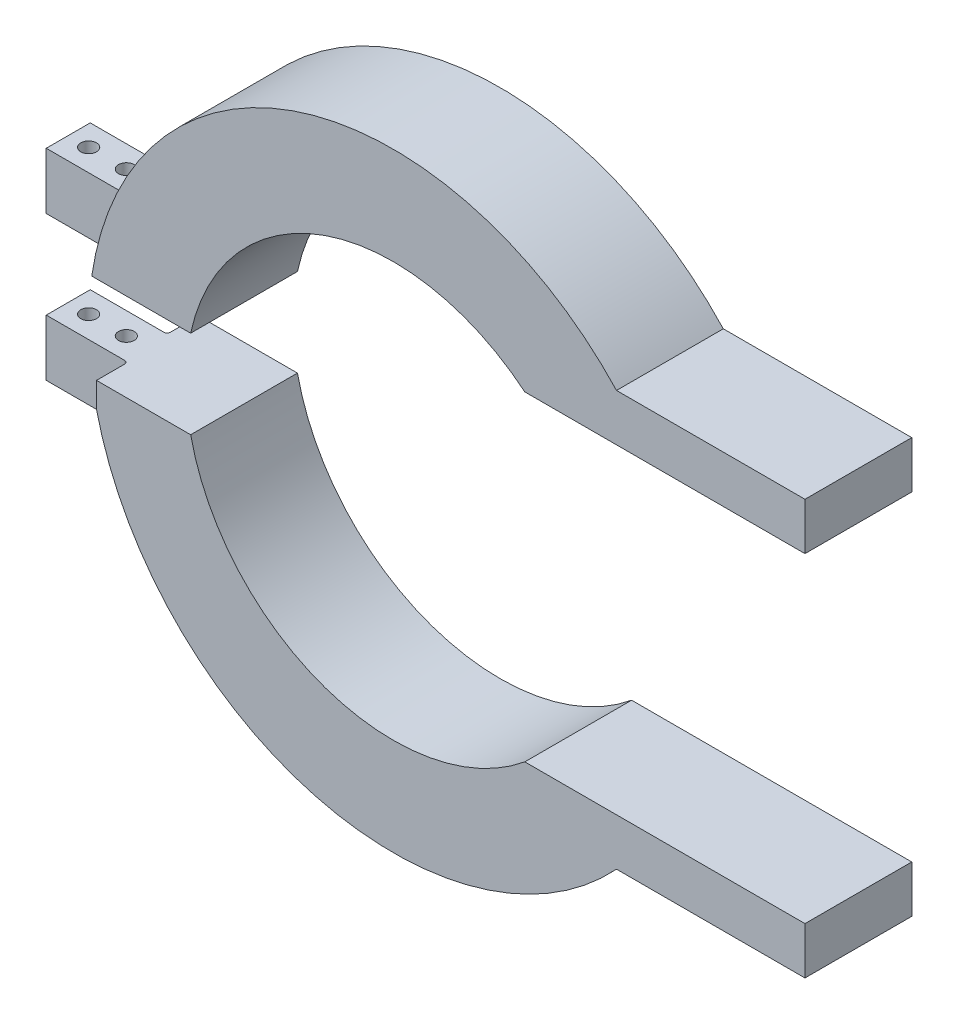
SolidWorks part; units mm, degrees
ref_plane "Front Plane" through (0, 0, 0) normal (0, 0, 1) x (1, 0, 0)
ref_plane "Top Plane" through (0, 0, 0) normal (0, 1, 0) x (1, 0, 0)
ref_plane "Right Plane" through (0, 0, 0) normal (1, 0, 0) x (0, 0, -1)
sketch "Sketch1" plane through (0, 0, 0) normal (0, 0, 1) x (1, 0, 0)
  line L0 (0, 0) -> (-48.5, 0) construction
  line L4 (35.5422, -33) -> (65.5422, -33)
  line L14 (-60.2361, -11) -> (-60.2361, -7)
  line L15 (20.9464, 25.5) -> (65.5422, 25.5)
  line L16 (20.9464, -25.5) -> (65.5422, -25.5)
  line L17 (65.5422, -33) -> (65.5422, -25.5)
  line L18 (-60.2361, 7) -> (-60.2361, 11)
  line L19 (0, 0) -> (88.5794, 0)
  line L21 (-47.2361, -11) -> (-60.2361, -11)
  line L22 (35.5422, 33) -> (65.5422, 33)
  line L23 (65.5422, 33) -> (65.5422, 25.5)
  line L25 (-60.2361, -7) -> (-32.249, -7)
  line L26 (-60.2361, 7) -> (-32.2494, 6.9983)
  line L27 (-47.2361, 11) -> (-60.2361, 11)
  arc A3 (35.5422, 33) -> (-47.2361, 11) centre (0, 0) ccw
  arc A5 (-47.2361, -11) -> (35.5422, -33) centre (0, 0) ccw
  arc A7 (20.9464, 25.5) -> (-32.2494, 6.9983) centre (0, 0) ccw
  arc A8 (-32.249, -7) -> (20.9464, -25.5) centre (0, 0) ccw
  point P17 (-48.5, 0)
  dimension "D1" = 48.5
  dimension "D6" = 7.5
  dimension "D4" = 48.5
  dimension "D5" = 66
  dimension "D3" = 30
  dimension "D7" = 4
  dimension "D2" = 51
  dimension "D8" = 22
  dimension "D9" = 13
extrude "Boss-Extrude1" add sketch "Sketch1" along normal blind 7 contours A7 L15 L23 L22 A3 L27 L18 L26 | A8 L25 L14 L21 A5 L4 L17 L16
sketch "Sketch2" plane through (0, 11, 0) normal (0, 1, 0) x (1, 0, 0)
  line L0 (-47.2361, -3.5) -> (-50.9861, -3.5) construction
  line L1 (-47.2361, -7) -> (-47.2361, 0) construction
  line L2 (-47.2361, -3.5) -> (-47.2361, 0) construction
  line L3 (-50.9861, -3.5) -> (-56.9861, -3.5) construction
  circle A0 centre (-50.9861, -3.5) radius 1.25
  circle A1 centre (-56.9861, -3.5) radius 1.25
  dimension "D2" = 6
  dimension "D3" = 2.5
  dimension "D4" = 2.5
  dimension "D1" = 3.75
sketch "Sketch7" plane through (0, 0, 7) normal (0, 0, 1) x (1, 0, 0)
  line L0 (-47.2361, -11) -> (-47.2361, -7)
  line L1 (-60.2361, -7) -> (-32.249, -7) construction
  line L2 (-47.2361, -7) -> (-32.249, -7)
  line L3 (35.5422, -33) -> (65.5422, -33)
  line L4 (65.5422, -33) -> (65.5422, -25.5) construction
  line L5 (35.5422, -33) -> (65.5422, -33) construction
  line L6 (65.5422, -33) -> (65.5422, -25.5)
  line L7 (20.9464, -25.5) -> (65.5422, -25.5)
  line L8 (20.9464, 25.5) -> (65.5422, 25.5)
  line L9 (20.9464, 25.5) -> (65.5422, 25.5) construction
  line L10 (65.5422, 25.5) -> (65.5422, 33)
  line L11 (65.5422, 33) -> (35.5422, 33)
  line L12 (-32.2494, 6.9983) -> (-47.9923, 6.9993)
  line L13 (-60.2361, 7) -> (-32.2494, 6.9983) construction
  arc A0 (-32.249, -7) -> (20.9464, -25.5) centre (0, 0) ccw
  arc A1 (-47.2361, -11) -> (35.5422, -33) centre (0, 0) ccw
  arc A2 (20.9464, 25.5) -> (-32.2494, 6.9983) centre (0, 0) ccw
  arc A3 (35.5422, 33) -> (-47.9923, 6.9993) centre (0, 0) ccw
extrude "Boss-Extrude2" add sketch "Sketch7" along normal blind 5
sketch "Sketch8" plane through (0, 0, 0) normal (0, 0, -1) x (-1, 0, 0)
  line L0 (32.249, -7) -> (47.9922, -7)
  line L1 (60.2361, -7) -> (32.249, -7) construction
  line L2 (-20.9464, -25.5) -> (-65.5422, -25.5)
  line L3 (-65.5422, -25.5) -> (-65.5422, -33)
  line L4 (-65.5422, -33) -> (-35.5422, -33)
  line L5 (-35.5422, -33) -> (-65.5422, -33) construction
  line L6 (-3.3458, 0) -> (4.69, 0)
  line L7 (32.249, 7) -> (47.9922, 7)
  line L8 (-20.9464, 25.5) -> (-65.5422, 25.5)
  line L9 (-65.5422, 25.5) -> (-65.5422, 33)
  line L10 (-65.5422, 33) -> (-35.5422, 33)
  arc A0 (-20.9464, -25.5) -> (32.249, -7) centre (0, 0) ccw
  arc A3 (-35.5422, -33) -> (47.9922, -7) centre (0, 0) ccw
  arc A4 (47.9922, 7) -> (-35.5422, 33) centre (0, 0) ccw
  arc A5 (32.249, 7) -> (-20.9464, 25.5) centre (0, 0) ccw
  arc M5 (32.249, -7) -> (-20.9464, -25.5) centre (0, 0) cw
  line M6 (-20.9464, -25.5) -> (-65.5422, -25.5)
  line M7 (-65.5422, -25.5) -> (-65.5422, -33)
  line M8 (-65.5422, -33) -> (-35.5422, -33)
  arc M9 (-35.5422, -33) -> (47.2361, -11) centre (0, 0) ccw
  line M12 (60.2361, -7) -> (32.249, -7)
extrude "Boss-Extrude3" add sketch "Sketch8" along normal blind 5 contours A5 L7 A4 L10 L9 L8 | A3 M9 M12 M5 M6 M7 M8
sketch "Sketch9" plane through (0, 11, 0) normal (0, 1, 0) x (1, 0, 0)
  line L0 (-47.2361, 0) -> (-60.2361, 0)
  line L1 (-60.2361, 0) -> (-60.2361, -7)
  line L2 (-60.2361, -7) -> (-47.2361, -7)
  line L3 (-47.2361, -7) -> (-47.2361, 0)
extrude "Boss-Extrude4" add sketch "Sketch9" along normal blind 5
sketch "Sketch10" plane through (0, -11, 0) normal (0, -1, 0) x (-1, 0, 0)
  line L0 (60.2361, -7) -> (60.2361, 0)
  line L1 (60.2361, 0) -> (47.2361, 0)
  line L2 (47.2361, 0) -> (47.2361, -7)
  line L3 (47.2361, -7) -> (60.2361, -7)
extrude "Boss-Extrude5" add sketch "Sketch10" along normal blind 5
sketch "Sketch11" plane through (0, 16, 0) normal (0, 1, 0) x (1, 0, 0)
  line L0 (-50.9861, -3.5) -> (-47.2361, -3.5) construction
  line L1 (-47.2361, -3.5) -> (-47.2361, 0) construction
  line L2 (-56.9861, -3.5) -> (-50.9861, -3.5) construction
  circle A0 centre (-56.9861, -3.5) radius 1.25
  circle A1 centre (-50.9861, -3.5) radius 1.25
extrude "Cut-Extrude2" cut sketch "Sketch11" against normal up to surface (32 mm away) up to face at (-53.7361, -16, 3.5)
sketch "Sketch12" plane through (-47.2361, 0, 0) normal (1, 0, 0) x (0, 0, -1)
  line L0 (0, 11) -> (0, 16)
  line L1 (-3.5, 11) -> (0, 11) construction
  line L2 (0, 16) -> (-7, 16)
  line L3 (-7, 16) -> (-7, 11)
  line L4 (-7, 16) -> (-7, 11) construction
  line L5 (-7, 11) -> (0, 11)
  line L6 (1.5401, 0) -> (-3.3761, 0)
  line L7 (0, -16) -> (-7, -16)
  line L8 (0, -11) -> (0, -16)
  line L9 (-7, -16) -> (-7, -11)
  line L10 (-7, -11) -> (0, -11)
extrude "Boss-Extrude6" add sketch "Sketch12" along normal up to surface contours L10 L9 L7 L8 | L3 L5 L0 L2 up to face at (-25.9213, -23.4556, 3)
fillet "Fillet3" radius 0.5 3 edges at (-47.1039, 11.5528, 0) (-45.7848, 16, 3.5) (-47.104, 11.5525, 7)
fillet "Fillet4" radius 0.5 4 edges at (-47.2361, -9, 7) (-46.5776, -13.5195, 7) (-45.7848, -16, 3.5) (-47.1039, -11.5528, 0)
